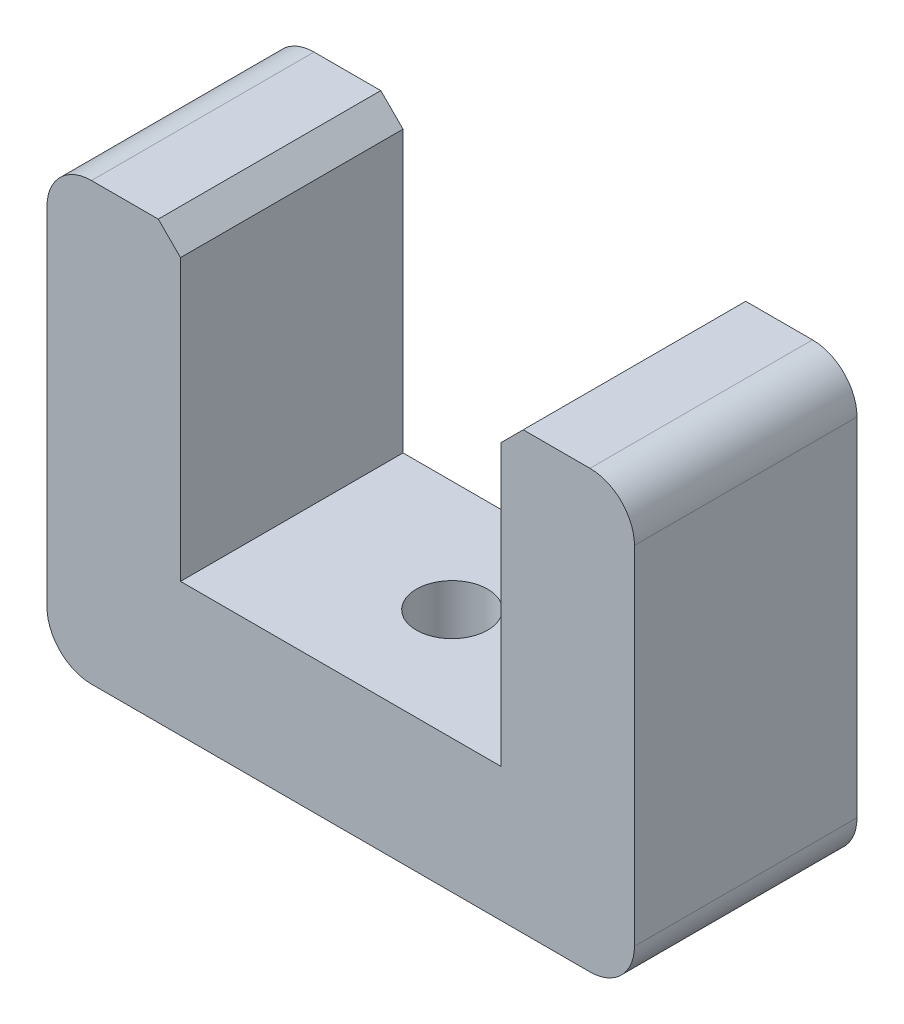
SolidWorks part; units mm, degrees
material "PLA"
ref_plane "前视基准面" through (0, 0, 0) normal (0, 0, 1) x (1, 0, 0)
ref_plane "上视基准面" through (0, 0, 0) normal (0, 1, 0) x (1, 0, 0)
ref_plane "右视基准面" through (0, 0, 0) normal (1, 0, 0) x (0, 0, -1)
sketch "草图2" plane through (0, 0, 0) normal (0, 0, 1) x (1, 0, 0)
  line L0 (0, 13.7862) -> (0, -11.809) construction
  line L1 (-11.858, 0) -> (10.8944, 0) construction
  line L2 (-3.6, 0) -> (-3.6, -6.8)
  line L3 (-3.6, -6.8) -> (3.6, -6.8)
  line L4 (-6.6, 0) -> (-6.6, -9.8)
  line L5 (-6.6, -9.8) -> (6.6, -9.8)
  line L7 (-3.6, 0) -> (-6.6, 0)
  line L8 (3.6, 0) -> (6.6, 0)
  line L9 (6.6, 0) -> (6.6, -9.8)
  line L10 (3.6, 0) -> (3.6, -6.8)
  dimension "D1" = 7.2
  dimension "D2" = 6.8
  dimension "D3" = 3
  dimension "D4" = 3
extrude "凸台-拉伸1" add sketch "草图2" along normal blind 5
chamfer "倒角1" distance 0.5 angle 45 2 edges at (-3.6, 0, 2.5) (3.6, 0, 2.5)
fillet "圆角1" radius 1 4 edges at (-6.6, -9.8, 2.5) (6.6, -9.8, 2.5) (-6.6, 0, 2.5) (6.6, 0, 2.5)
sketch "草图3" plane through (0, -6.8, 0) normal (0, 1, 0) x (1, 0, 0)
  line L0 (0, 2.1791) -> (0, -6.0161) construction
  line L1 (-3.2544, -2.5) -> (2.6592, -2.5) construction
  line L2 (3.6, 0) -> (-3.6, 0) construction
  circle A0 centre (0, -2.5) radius 0.8
  dimension "D2" = 1.6
  dimension "D1" = 2.5
extrude "切除-拉伸1" cut sketch "草图3" against normal blind 4
